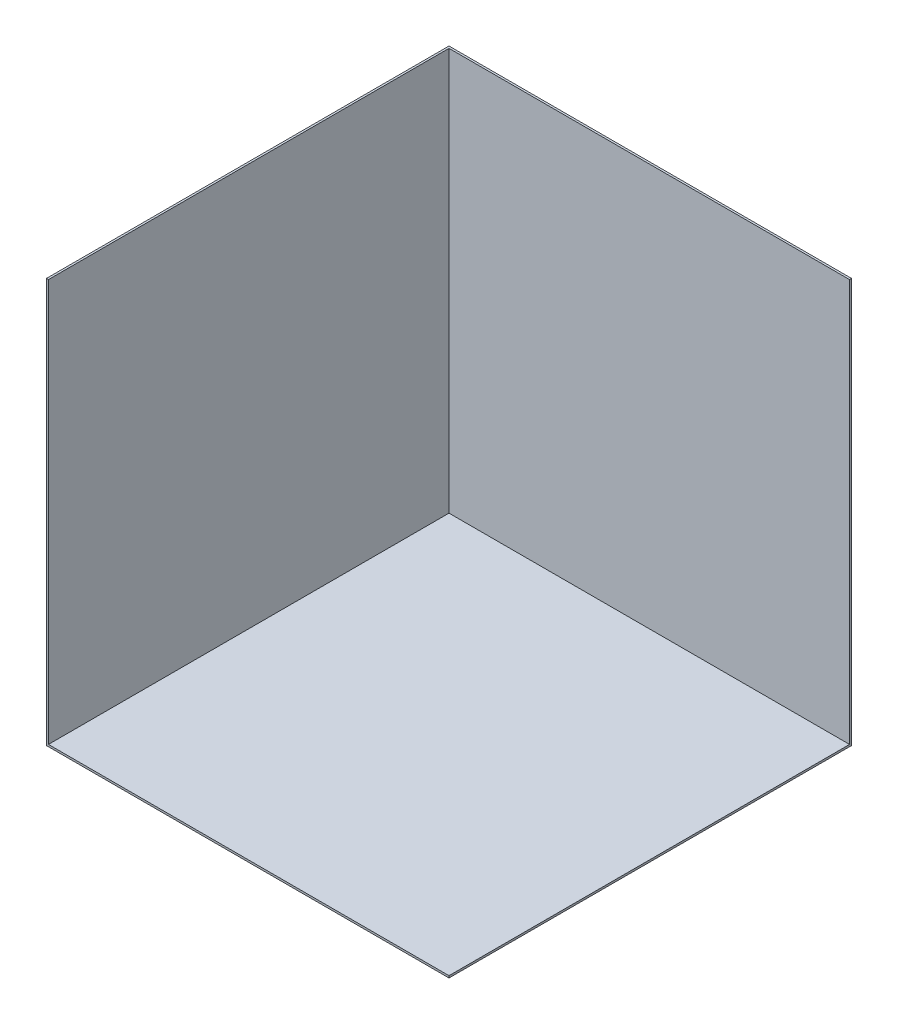
SolidWorks part; units mm, degrees
ref_plane "Front Plane" through (0, 0, 0) normal (0, 0, 1) x (1, 0, 0)
ref_plane "Top Plane" through (0, 0, 0) normal (0, 1, 0) x (1, 0, 0)
ref_plane "Right Plane" through (0, 0, 0) normal (1, 0, 0) x (0, 0, -1)
sketch "Sketch1" plane through (0, 0, 0) normal (0, 1, 0) x (1, 0, 0)
  line L1 (-2000, 2000) -> (0, 2000)
  line L2 (-2000, 2000) -> (-2000, 0)
  line L3 (-2000, 0) -> (0, 0)
  line L4 (0, 2000) -> (0, 0)
  line L5 (-2000, 2000) -> (0, 0) construction
  line L6 (-2000, 0) -> (0, 2000) construction
  point P0 (-1000, 1000)
extrude "Boss-Extrude1" add sketch "Sketch1" along normal blind 10
sketch "Sketch2" plane through (0, 10, 0) normal (0, 1, 0) x (1, 0, 0)
  line L0 (-2000, 0) -> (0, 0) construction
  line L1 (-2000, 2000) -> (-1990, 2000)
  line L2 (-2000, 2000) -> (-2000, 0)
  line L3 (-2000, 0) -> (-1990, 0)
  line L4 (-1990, 2000) -> (-1990, 0)
  line L6 (0, 2000) -> (-2000, 2000)
  line L7 (0, 2000) -> (0, 1990)
  line L8 (0, 1990) -> (-2000, 1990)
  line L9 (-2000, 2000) -> (-2000, 1990)
  line M1 (0, 0) -> (0, 2000)
  line M2 (0, 2000) -> (-2000, 2000)
  line M3 (-2000, 2000) -> (-2000, 0)
  line M4 (-2000, 0) -> (0, 0)
extrude "Boss-Extrude2" add sketch "Sketch2" along normal blind 2000 contours L8 L4 M1 M2 | L8 L4 M2 M3 | L4 L8 L2 M4
